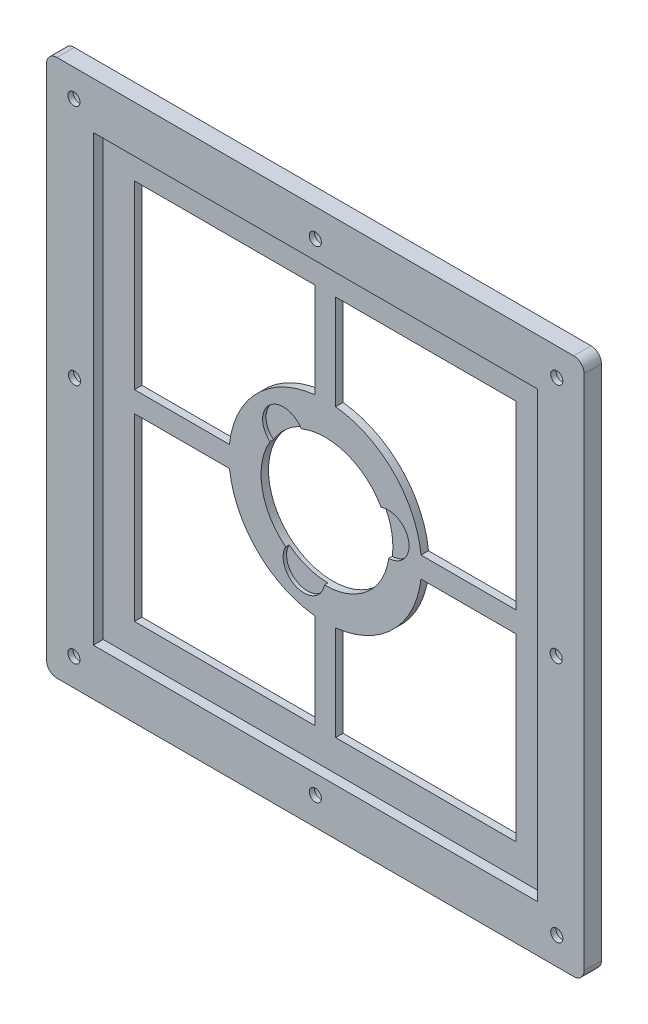
SolidWorks part; units mm, degrees
ref_plane "Спереди" through (0, 0, 0) normal (0, 0, 1) x (1, 0, 0)
ref_plane "Сверху" through (0, 0, 0) normal (0, 1, 0) x (1, 0, 0)
ref_plane "Справа" through (0, 0, 0) normal (1, 0, 0) x (0, 0, -1)
sketch "Sketch1" plane through (0, 0, 0) normal (0, 0, 1) x (1, 0, 0)
  line L1 (-63.5, 63.5) -> (63.5, 63.5) construction
  line L2 (-63.5, 63.5) -> (-63.5, -63.5) construction
  line L3 (-63.5, -63.5) -> (63.5, -63.5) construction
  line L4 (63.5, 63.5) -> (63.5, -63.5) construction
  line L5 (-63.5, 63.5) -> (63.5, -63.5) construction
  line L6 (-63.5, -63.5) -> (63.5, 63.5) construction
  line L7 (-77.5, 77.5) -> (77.5, 77.5)
  line L8 (-77.5, 77.5) -> (-77.5, -77.5)
  line L9 (-77.5, -77.5) -> (77.5, -77.5)
  line L10 (77.5, 77.5) -> (77.5, -77.5)
  line L11 (-77.5, 77.5) -> (77.5, -77.5) construction
  line L12 (-77.5, -77.5) -> (77.5, 77.5) construction
  line L17 (-55, 55) -> (55, 55)
  line L18 (-55, 55) -> (-55, -55)
  line L19 (-55, -55) -> (55, -55)
  line L20 (55, 55) -> (55, -55)
  line L21 (-55, 55) -> (55, -55) construction
  line L22 (-55, -55) -> (55, 55) construction
  line L23 (-50, 50) -> (50, 50) construction
  line L24 (-50, 50) -> (-50, -50) construction
  line L25 (-50, -50) -> (50, -50) construction
  line L26 (50, 50) -> (50, -50) construction
  line L27 (-50, 50) -> (50, -50) construction
  line L28 (-50, -50) -> (50, 50) construction
  circle A0 centre (-50, 50) radius 1.5
  circle A1 centre (50, 50) radius 1.5
  circle A2 centre (50, -50) radius 1.5
  circle A3 centre (-50, -50) radius 1.5
  point P0 (0, 0)
  point P6 (0, 0)
  point P11 (0, 0)
  point P12 (0, 0)
  point P17 (0, 0)
  point P32 (0, 0)
  dimension "D1" = 127
  dimension "D2" = 155
  dimension "D3" = 110
  dimension "D4" = 100
  dimension "D5" = 4
extrude "Boss-Extrude1" add sketch "Sketch1" along normal blind 5 contours A0 | L10 L7 L8 L9 A3 A2 A1 A0 L17 L20 L19 L18 | A1 | A2 | A3
sketch "Sketch3" plane through (0, 0, 5) normal (0, 0, 1) x (1, 0, 0)
  line L1 (-64, 64) -> (64, 64)
  line L2 (-64, 64) -> (-64, -64)
  line L3 (-64, -64) -> (64, -64)
  line L4 (64, 64) -> (64, -64)
  line L5 (-64, 64) -> (64, -64) construction
  line L6 (-64, -64) -> (64, 64) construction
  point P0 (0, 0)
  dimension "D1" = 128
extrude "Cut-Extrude2" cut sketch "Sketch3" against normal blind 2.85
fillet "Fillet1" radius 3 4 edges at (-77.5, -77.5, 2.5) (77.5, -77.5, 2.5) (77.5, 77.5, 2.5) (-77.5, 77.5, 2.5)
sketch "Sketch4" plane through (0, 0, 2.15) normal (0, 0, -1) x (-1, 0, 0)
  circle A0 centre (-50, 50) radius 2.5
  circle A1 centre (50, 50) radius 2.5
  circle A2 centre (50, -50) radius 2.5
  circle A3 centre (-50, -50) radius 2.5
  point P12 (0, 0)
  dimension "D1" = 4
extrude "Cut-Extrude3" [suppressed] cut sketch "Sketch4" along normal blind 2.5
sketch "Sketch5" plane through (0, 0, 8) normal (0, 0, 1) x (1, 0, 0)
  line L0 (0, 0) -> (0, 69.4313) construction
  line L1 (0, 0) -> (-69.6102, 69.6102) construction
  circle A0 centre (0, 69.4313) radius 1.75
  circle A1 centre (-69.6102, 69.6102) radius 1.75
  circle A2 centre (69.4313, 0) radius 1.75
  circle A3 centre (69.6102, 69.6102) radius 1.75
  circle A4 centre (0, -69.4313) radius 1.75
  circle A5 centre (69.6102, -69.6102) radius 1.75
  circle A6 centre (-69.4313, 0) radius 1.75
  circle A7 centre (-69.6102, -69.6102) radius 1.75
  point P23 (0, 0)
  dimension "D1" = 4
extrude "Cut-Extrude4" cut sketch "Sketch5" against normal blind 23
sketch "Sketch6" plane through (0, 0, 0) normal (0, 0, -1) x (-1, 0, 0)
  circle A0 centre (-69.6102, 69.6102) radius 3.35
  circle A1 centre (69.6102, 69.6102) radius 3.35
  circle A2 centre (69.6102, -69.6102) radius 3.35
  circle A3 centre (-69.6102, -69.6102) radius 3.35
  circle A4 centre (-69.4313, 0) radius 3.35
  circle A5 centre (0, 69.4313) radius 3.35
  circle A6 centre (69.4313, 0) radius 3.35
  circle A7 centre (0, -69.4313) radius 3.35
  point P12 (0, 0)
  point P22 (0, 0)
  dimension "D1" = 4
  dimension "D2" = 4
extrude "Cut-Extrude5" cut sketch "Sketch6" against normal blind 3.5
sketch "Sketch7" plane through (0, 0, 2.15) normal (0, 0, 1) x (1, 0, 0)
  circle A0 centre (0, 0) radius 18.5
  circle A1 centre (-12.337, 13.7858) radius 6 construction
  circle A4 centre (0, 0) radius 27.7679
  point P11 (0, 0)
extrude "Boss-Extrude3" add sketch "Sketch7" against normal up to surface (2.15 mm away) separate body contours A4 A0
sketch "Sketch8" plane through (0, 0, 2.15) normal (0, 0, 1) x (1, 0, 0)
  circle A0 centre (-12.0533, 14.0346) radius 6
  circle A1 centre (0, 0) radius 18.5 construction
  circle A2 centre (18.1809, 3.4211) radius 6
  circle A3 centre (-6.1277, -17.4557) radius 6
  point P5 (16.5862, 8.1944)
  point P6 (18.1809, 3.4211)
  point P10 (0, 0)
  dimension "D1" = 3
extrude "Cut-Extrude6" cut sketch "Sketch8" against normal blind 1
sketch "Sketch9" plane through (0, 0, 2.15) normal (0, 0, 1) x (1, 0, 0)
  line L0 (56.0954, 2.8848) -> (25.3778, 2.8848)
  line L1 (-3, 55.9802) -> (3, 55.9802)
  line L2 (-3, 55.9802) -> (-3, 25.2626)
  line L3 (-3, 25.2626) -> (3, 25.2626)
  line L4 (3, 55.9802) -> (3, 25.2626)
  line L5 (-3, 55.9802) -> (3, 25.2626) construction
  line L6 (-3, 25.2626) -> (3, 55.9802) construction
  line L7 (56.0954, 2.8848) -> (56.0954, -3.1152)
  line L8 (56.0954, -3.1152) -> (25.3778, -3.1152)
  line L9 (25.3778, 2.8848) -> (25.3778, -3.1152)
  line L10 (3, -56.2106) -> (3, -25.493)
  line L11 (3, -56.2106) -> (-3, -56.2106)
  line L12 (-3, -56.2106) -> (-3, -25.493)
  line L13 (3, -25.493) -> (-3, -25.493)
  line L14 (-56.0954, -3.1152) -> (-25.3778, -3.1152)
  line L15 (-56.0954, -3.1152) -> (-56.0954, 2.8848)
  line L16 (-56.0954, 2.8848) -> (-25.3778, 2.8848)
  line L17 (-25.3778, -3.1152) -> (-25.3778, 2.8848)
  point P0 (0, 40.6214)
  point P5 (0, 0)
  point P6 (1.196, 46.2758)
  point P7 (0, 40.6214)
  point P20 (0, -0.1152)
  dimension "D1" = 4
extrude "Boss-Extrude4" add sketch "Sketch9" against normal up to surface (2.15 mm away)
sketch "Sketch10" plane through (0, 0, 2.15) normal (0, 0, 1) x (1, 0, 0)
  circle A0 centre (-50, 50) radius 2.316
  circle A1 centre (50, 50) radius 2.316
  circle A2 centre (50, -50) radius 2.316
  circle A3 centre (-50, -50) radius 2.316
  point P12 (0, 0)
  dimension "D1" = 4
extrude "Cut-Extrude7" cut sketch "Sketch10" against normal through all both and the other way through all
